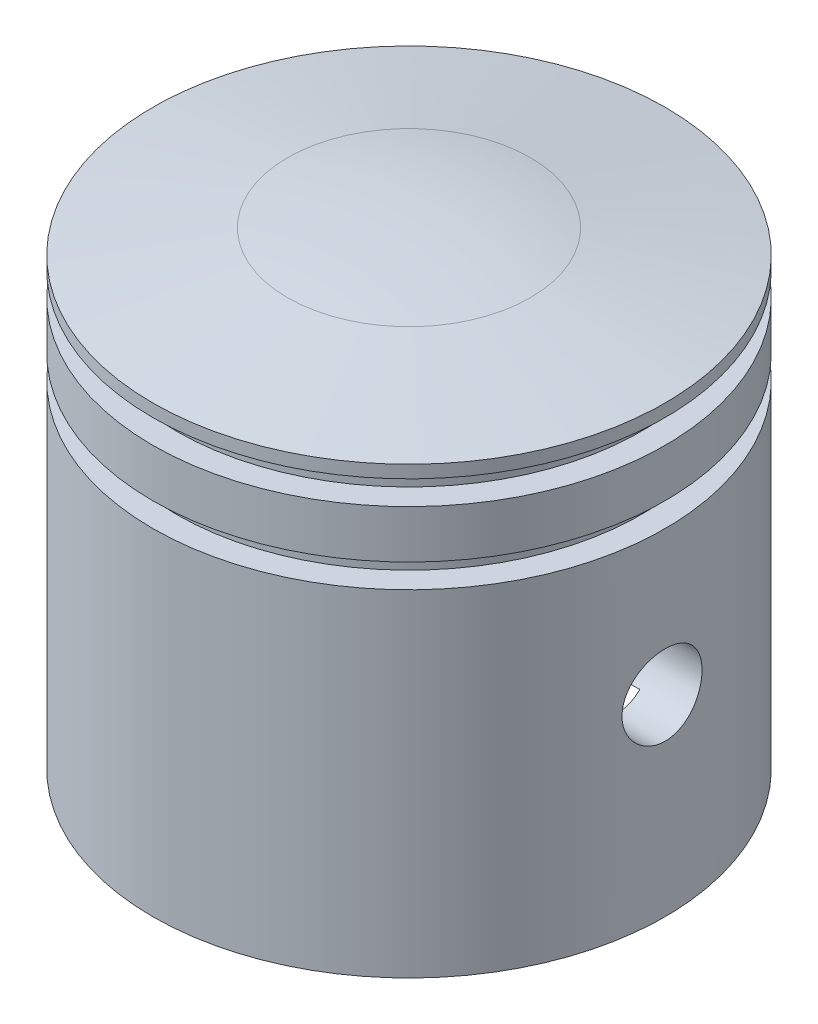
SolidWorks part; units mm, degrees
ref_plane "Front Plane" through (0, 0, 0) normal (0, 0, 1) x (1, 0, 0)
ref_plane "Top Plane" through (0, 0, 0) normal (0, 1, 0) x (1, 0, 0)
ref_plane "Right Plane" through (0, 0, 0) normal (1, 0, 0) x (0, 0, -1)
sketch "Sketch1" plane through (0, 0, 0) normal (0, 0, 1) x (1, 0, 0)
  line L0 (0, 0) -> (16, 0)
  line L1 (16, 0) -> (16, 27.7905)
  line L2 (16, 27.7905) -> (7.581, 29.275)
  line L4 (0, 30) -> (0, 0)
  line L5 (0, 30) -> (24.7766, 30) construction
  arc A1 (7.581, 29.275) -> (0, 30) centre (0, -10) ccw
  point P8 (0, 0)
  point P9 (0, 0)
  point P10 (0, 0)
  point P11 (0, 0)
  dimension "D1" = 30
  dimension "D2" = 16
  dimension "D3" = 10
revolve "Revolve1" add sketch "Sketch1" angle 360 about L4
sketch "Sketch2" plane through (0, 0, 0) normal (0, 0, 1) x (1, 0, 0)
  line L0 (0, 0) -> (0, 28.7718) construction
  line L2 (14.5, 27) -> (19.2164, 27)
  line L3 (14.5, 27) -> (14.5, 25.5)
  line L4 (14.5, 25.5) -> (19.2164, 25.5)
  line L5 (19.2164, 27) -> (19.2164, 25.5)
  line L6 (14.5, 22.5) -> (19.2164, 22.5)
  line L7 (14.5, 22.5) -> (14.5, 21)
  line L8 (14.5, 21) -> (19.2164, 21)
  line L9 (19.2164, 22.5) -> (19.2164, 21)
  point P11 (14.5, 21.75)
  dimension "D1" = 3
  dimension "D2" = 1.5
  dimension "D3" = 1.5
  dimension "D4" = 21
  dimension "D5" = 14.5
revolve "Cut-Revolve1" cut sketch "Sketch2" angle 360 about L0
sketch "Sketch3" plane through (0, 0, 0) normal (0, -1, 0) x (1, 0, 0)
  circle A0 centre (0, 0) radius 10
extrude "Cut-Extrude1" cut sketch "Sketch3" against normal blind 24
sketch "Sketch4" plane through (0, 0, 0) normal (0, -1, 0) x (1, 0, 0)
  circle A0 centre (0, 0) radius 13
extrude "Cut-Extrude2" cut sketch "Sketch4" against normal blind 10
sketch "Sketch5" plane through (0, 0, 0) normal (1, 0, 0) x (0, 0, -1)
  circle A0 centre (0, 12) radius 2.5
  point P2 (0, 0)
  dimension "D1" = 12
extrude "Cut-Extrude3" cut sketch "Sketch5" against normal through all both and the other way through all
